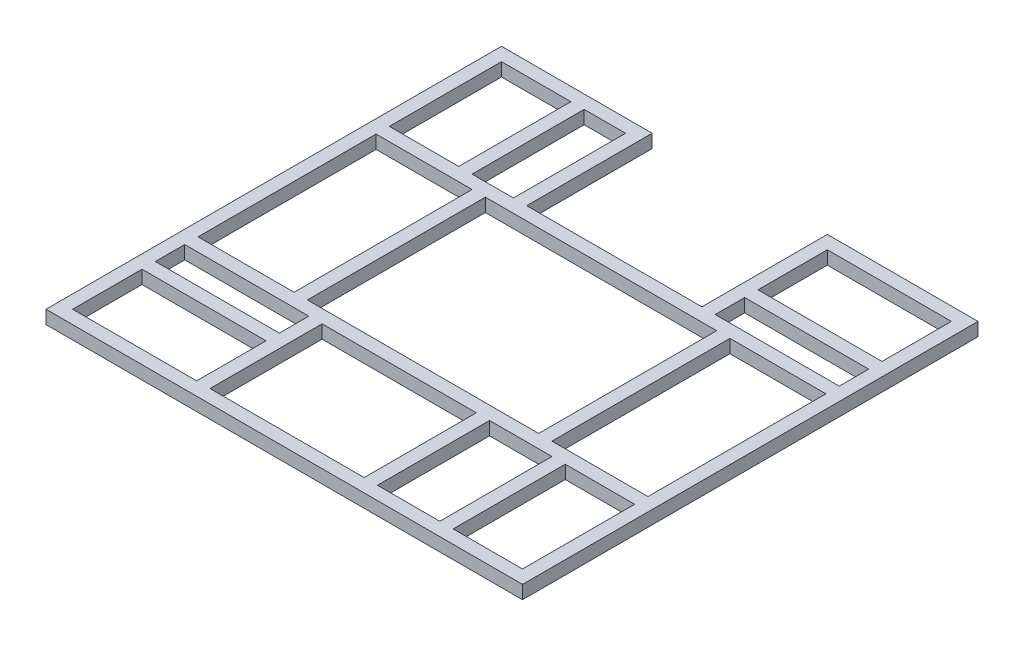
SolidWorks part; units mm, degrees
ref_plane "Front Plane" through (0, 0, 0) normal (0, 0, 1) x (1, 0, 0)
ref_plane "Top Plane" through (0, 0, 0) normal (0, 1, 0) x (1, 0, 0)
ref_plane "Right Plane" through (0, 0, 0) normal (1, 0, 0) x (0, 0, -1)
sketch "Sketch1" plane through (0, 0, 0) normal (0, 1, 0) x (1, 0, 0)
  line L0 (-184, 127) -> (-184, -127)
  line L1 (-340, -325) -> (340, -325)
  line L2 (-340, -325) -> (-340, 325)
  line L3 (-340, 325) -> (-125, 325)
  line L4 (340, -325) -> (340, 325)
  line L5 (-321, -306.8382) -> (-152.7385, -146) construction
  line L6 (-340, 325) -> (-152.7385, 146) construction
  line L7 (-165, 127) -> (-165, -127)
  line L8 (-321, 306) -> (-321, 146)
  line L9 (321, 306.8382) -> (321, 207)
  line L10 (-144, 306) -> (-144, 146)
  line L11 (125, 325) -> (125, 146)
  line L12 (-321, 306) -> (-222, 306)
  line L13 (125, 325) -> (340, 325)
  line L14 (-321, -306) -> (-144, -306)
  line L15 (321, -306) -> (222, -306)
  line L16 (-125, -306) -> (95, -306)
  line L17 (144, 306) -> (321, 306)
  line L18 (-222, 306) -> (-222, 146)
  line L20 (-321, 146) -> (-222, 146)
  line L21 (-321, 127) -> (-184, 127)
  line L22 (114, -146) -> (203, -146)
  line L23 (-296, 162.5) -> (-256, 162.5) construction
  line L24 (-296, 162.5) -> (-296, 289.5) construction
  line L25 (-296, 289.5) -> (-256, 289.5) construction
  line L26 (-256, 162.5) -> (-256, 289.5) construction
  line L27 (-296, 162.5) -> (-256, 289.5) construction
  line L28 (-296, 289.5) -> (-256, 162.5) construction
  line L29 (114, -127) -> (165, -127)
  line L32 (-144, -146) -> (-321, -146)
  line L33 (222, -146) -> (222, -306)
  line L34 (203, -146) -> (203, -306)
  line L35 (-144, -127) -> (-165, -127)
  line L36 (256, -289.5) -> (296, -289.5) construction
  line L37 (256, -289.5) -> (256, -162.5) construction
  line L38 (256, -162.5) -> (296, -162.5) construction
  line L39 (296, -289.5) -> (296, -162.5) construction
  line L40 (256, -289.5) -> (296, -162.5) construction
  line L41 (256, -162.5) -> (296, -289.5) construction
  line L42 (-321, -188) -> (-144, -188)
  line L43 (-321, -207) -> (-144, -207)
  line L44 (144, 146) -> (321, 146)
  line L45 (-296, -241) -> (-169, -241) construction
  line L46 (-296, -241) -> (-296, -281) construction
  line L47 (-296, -281) -> (-169, -281) construction
  line L48 (-169, -241) -> (-169, -281) construction
  line L49 (-296, -241) -> (-169, -281) construction
  line L50 (-296, -281) -> (-169, -241) construction
  line L51 (132.8615, 127) -> (165, 127)
  line L52 (144, 207) -> (321, 207)
  line L53 (144, 188) -> (321, 188)
  line L54 (-203, 306) -> (-203, 146)
  line L55 (165, 241) -> (292, 241) construction
  line L56 (165, 241) -> (165, 281) construction
  line L57 (165, 281) -> (292, 281) construction
  line L58 (292, 241) -> (292, 281) construction
  line L59 (165, 241) -> (292, 281) construction
  line L60 (165, 281) -> (292, 241) construction
  line L61 (-125, -127) -> (95, -127)
  line L62 (-125, -146) -> (95, -146)
  line L63 (-144, -146) -> (-144, -188)
  line L64 (-125, -306) -> (-125, -146)
  line L65 (-125, 146) -> (125, 146)
  line L66 (321, 188) -> (321, 146)
  line L67 (-125, 325) -> (-125, 146)
  line L68 (144, 146) -> (144, 188)
  line L69 (165, 127) -> (165, -127)
  line L70 (184, 127) -> (184, -127)
  line L71 (-125, -127) -> (-144, -127)
  line L72 (95, -127) -> (114, -127)
  line L73 (114, -146) -> (114, -306)
  line L74 (95, -146) -> (95, -306)
  line L75 (144, 207) -> (144, 306)
  line L77 (-321, 127) -> (-321, -127)
  line L78 (-165, 127) -> (132.8615, 127)
  line L79 (0, 0) -> (340, -325) construction
  line L80 (184, 127) -> (321, 127)
  line L81 (321, 127) -> (321, -127)
  line L82 (184, -127) -> (321, -127)
  line L83 (321, -146) -> (321, -306.8382)
  line L84 (-132.8615, -127) -> (321, 306.8382) construction
  line L85 (222, -146) -> (321, -146)
  line L86 (203, -306) -> (114, -306)
  line L87 (-184, -127) -> (-321, -127)
  line L88 (-321, -207) -> (-321, -306.8382)
  line L89 (-144, -207) -> (-144, -306)
  line L90 (-321, -146) -> (-321, -188)
  line L91 (-203, 146) -> (-144, 146)
  line L92 (-203, 306) -> (-144, 306)
  point P0 (0, 0)
  point P29 (-276, 226)
  point P52 (276, -226)
  point P62 (-262.9974, -251.3945)
  point P67 (-232.5, -207)
  point P68 (-232.5, -241)
  point P70 (222, -226)
  point P71 (-222, 226)
  point P72 (-256, 226)
  point P80 (232.5, 253.6173)
  point P86 (232.5, 207)
  dimension "D1" = 680
  dimension "D2" = 650
  dimension "D4" = 19
  dimension "D5" = 19
  dimension "D6" = 215
  dimension "D7" = 19
  dimension "D8" = 19
  dimension "D9" = 19
  dimension "D10" = 19
  dimension "D11" = 19
  dimension "D12" = 19
  dimension "D13" = 19
  dimension "D14" = 19
  dimension "D15" = 34
  dimension "D16" = 40
  dimension "D17" = 127
  dimension "D18" = 160
  dimension "D19" = 19
  dimension "D20" = 19
  dimension "D21" = 160
  dimension "D22" = 40
  dimension "D23" = 127
  dimension "D24" = 25
  dimension "D25" = 25
  dimension "D26" = 34
  dimension "D27" = 19
  dimension "D28" = 40
  dimension "D29" = 127
  dimension "D30" = 34
  dimension "D31" = 25
  dimension "D32" = 40
  dimension "D33" = 127
  dimension "D34" = 34
  dimension "D35" = 19
  dimension "D36" = 25
  dimension "D39" = 215
  dimension "D40" = 19
  dimension "D41" = 175
  dimension "D42" = 175
  dimension "D43" = 220
  dimension "D44" = 19
  dimension "D45" = 19
extrude "Boss-Extrude1" add sketch "Sketch1" along normal blind 19
